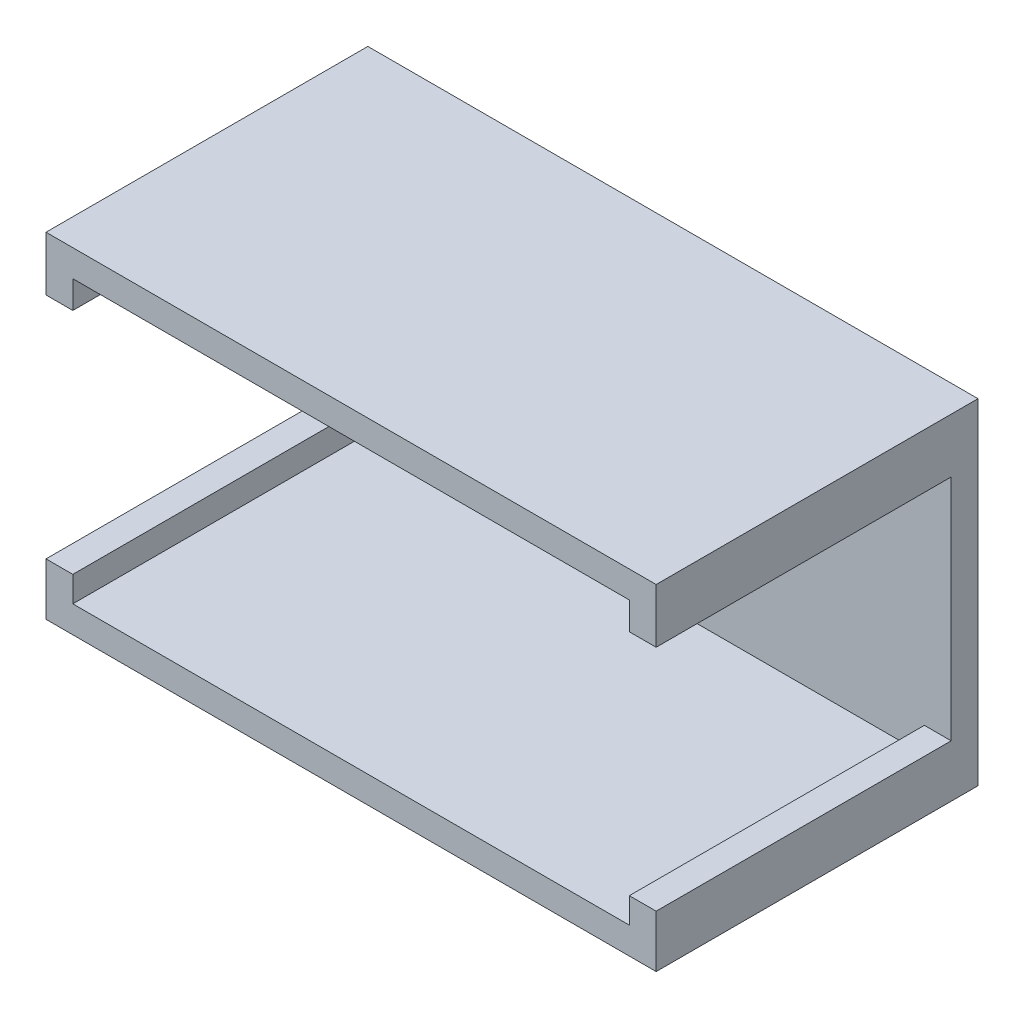
SolidWorks part; units mm, degrees
ref_plane "Alzado" through (0, 0, 0) normal (0, 0, 1) x (1, 0, 0)
ref_plane "Planta" through (0, 0, 0) normal (0, 1, 0) x (1, 0, 0)
ref_plane "Vista lateral" through (0, 0, 0) normal (1, 0, 0) x (0, 0, -1)
sketch "Croquis1" plane through (0, 0, 0) normal (0, 0, 1) x (1, 0, 0)
  line L0 (-48.9396, 26.5035) -> (-8.4396, 26.5035)
  line L1 (-49.9396, 5.5035) -> (-49.9396, 1.5035)
  line L2 (-48.9396, 26.5035) -> (-49.9396, 26.5035)
  line L6 (-8.4396, 26.5035) -> (-4.4396, 26.5035)
  line L7 (-49.9396, 26.5035) -> (-49.9396, 5.5035)
  line L8 (-4.4396, 26.5035) -> (-4.4396, 1.5035)
  line L9 (-8.4396, 1.5035) -> (-49.9396, 1.5035)
  line L10 (-4.4396, 1.5035) -> (-8.4396, 1.5035)
extrude "Saliente-Extruir1" add sketch "Croquis1" along normal blind 2
sketch "Croquis3" plane through (0, 0, 0) normal (0, 0, 1) x (1, 0, 0)
  line L0 (-48.9396, 26.5035) -> (-8.4396, 26.5035)
  line L1 (-49.9396, 26.5035) -> (-49.9396, 1.5035)
  line L2 (-10.4396, 3.5035) -> (-47.9396, 3.5035)
  line L3 (-8.4396, 26.5035) -> (-4.4396, 26.5035)
  line L5 (-4.4396, 26.5035) -> (-4.4396, 1.5035)
  line L6 (-10.4396, 24.5035) -> (-6.4396, 24.5035)
  line L7 (-6.4396, 24.5035) -> (-6.4396, 3.5035)
  line L8 (-6.4396, 3.5035) -> (-10.4396, 3.5035)
  line L9 (-49.9396, 1.5035) -> (-4.4396, 1.5035) construction
  line L10 (-4.4396, 1.5035) -> (-49.9396, 1.5035)
  line L12 (-47.9396, 3.5035) -> (-47.9396, 5.5035)
  line L16 (-49.9396, 26.5035) -> (-48.9396, 26.5035)
  line L21 (-47.9396, 5.5035) -> (-47.9396, 24.5035)
  line L22 (-47.9396, 24.5035) -> (-47.9396, 24.5035)
  line L23 (-47.9396, 24.5035) -> (-10.4396, 24.5035)
  line L27 (-49.9396, 5.5035) -> (-49.9396, 26.5035) construction
  line L28 (-49.9396, 1.5035) -> (-49.9396, 5.5035) construction
  line L29 (-8.4396, 6.5035) -> (-8.4396, 26.5035) construction
  line L30 (-8.4396, 5.5035) -> (-8.4396, 1.5035) construction
  line L31 (-8.4396, 6.5035) -> (-8.4396, 5.5035) construction
  line L32 (-10.4396, 6.5035) -> (-10.4396, 24.5035) construction
  line L33 (-10.4396, 6.5035) -> (-10.4396, 5.5035) construction
  line L34 (-10.4396, 5.5035) -> (-10.4396, 3.5035) construction
  line L36 (-8.4396, 1.5035) -> (-49.9396, 1.5035) construction
extrude "Saliente-Extruir2" add sketch "Croquis3" along normal blind 24
sketch "Croquis4" plane through (0, 0, 0) normal (1, 0, 0) x (0, 0, -1)
  line L0 (-2, 5.4077) -> (-28.8385, 5.4077)
  line L2 (-28.8385, 5.4077) -> (-28.8385, 22.4485)
  line L3 (-2, 22.4485) -> (-28.8385, 22.4485)
  line L4 (-2, 5.4077) -> (-2, 22.4485)
extrude "Cortar-Extruir1" cut sketch "Croquis4" against normal blind 70.1
ref_plane "Plano1" through (0, 26.5035, 0) normal (0, 1, 0) x (1, 0, 0)
sketch "Croquis5" plane through (0, 26.5035, 0) normal (0, 1, 0) x (1, 0, 0)
  line L0 (-49.9396, -20.6072) -> (-4.4396, -20.6072)
  line L2 (-49.9396, -24) -> (-49.9396, 0) construction
  line L3 (-49.9396, -20.6072) -> (-49.9396, -36.1)
  line L4 (-4.4396, -24) -> (-4.4396, 0) construction
  line L5 (-48.9396, -36.1) -> (-8.4396, -36.1)
  line L6 (-4.4396, -20.6072) -> (-4.4396, -36.1)
  line L7 (-4.4396, -36.1) -> (-8.4396, -36.1)
  line L12 (-49.9396, -36.1) -> (-48.9396, -36.1)
extrude "Saliente-Extruir3" add sketch "Croquis5" against normal blind 2
ref_plane "Plano2" through (0, 0, 36.1) normal (0, 0, 1) x (1, 0, 0)
sketch "Croquis6" plane through (0, 0, 36.1) normal (0, 0, 1) x (1, 0, 0)
  line L0 (-4.4396, 24.5035) -> (-49.9396, 24.5035)
  line L1 (-49.9396, 24.5035) -> (-49.9396, 33.5035)
  line L2 (-4.4396, 24.5035) -> (-4.4396, 33.5035)
  line L4 (-48.9396, 33.5035) -> (-8.4396, 33.5035)
  line L6 (-49.9396, 33.5035) -> (-48.9396, 33.5035)
  line L7 (-4.4396, 33.5035) -> (-8.4396, 33.5035)
extrude "Saliente-Extruir4" add sketch "Croquis6" against normal blind 2
sketch "Croquis7" plane through (0, 0, 36.1) normal (0, 0, 1) x (1, 0, 0)
  line L0 (-4.4396, 33.5035) -> (-49.9396, 33.5035)
  line L1 (-4.4396, 33.5035) -> (-4.4396, 31.5035)
  line L2 (-4.4396, 31.5035) -> (-49.9396, 31.5035)
  line L3 (-4.4396, 24.5035) -> (-4.4396, 33.5035) construction
  line L5 (-49.9396, 24.5035) -> (-49.9396, 33.5035) construction
  line L6 (-49.9396, 31.5035) -> (-49.9396, 33.5035)
extrude "Saliente-Extruir5" add sketch "Croquis7" against normal blind 8
sketch "Croquis8" plane through (0, 0, 36.1) normal (0, 0, 1) x (1, 0, 0)
  line L0 (-49.9396, 29.5035) -> (-49.9396, 26.5035)
  line L1 (-8.4396, 29.5035) -> (-4.4396, 29.5035)
  line L2 (-49.715, 29.5035) -> (-8.4396, 29.5035)
  line L3 (-49.9396, 24.5035) -> (-49.9396, 33.5035) construction
  line L5 (-8.4396, 26.5035) -> (-49.715, 26.5035)
  line L6 (-4.4396, 24.5035) -> (-4.4396, 33.5035) construction
  line L7 (18.755, 26.5035) -> (-18.755, 26.5035) construction
  line L8 (-49.9396, 26.5035) -> (-49.715, 26.5035)
  line L9 (-49.715, 29.5035) -> (-49.9396, 29.5035)
  line L10 (-4.4396, 29.5035) -> (-4.4396, 26.5035)
  line L11 (-4.4396, 26.5035) -> (-8.4396, 26.5035)
extrude "Saliente-Extruir6" add sketch "Croquis8" against normal blind 6
ref_plane "Plano4" through (0, 0, 24) normal (0, 0, 1) x (1, 0, 0)
sketch "Croquis9" plane through (0, 0, 24) normal (0, 0, 1) x (1, 0, 0)
  line L1 (13.0935, 53.3426) -> (-63.8689, 53.3426)
  line L2 (13.0935, 53.3426) -> (13.0935, -5.6152)
  line L3 (13.0935, -5.6152) -> (-63.8689, -5.6152)
  line L4 (-63.8689, 53.3426) -> (-63.8689, -5.6152)
extrude "Cortar-Extruir2" cut sketch "Croquis9" along normal blind 28
